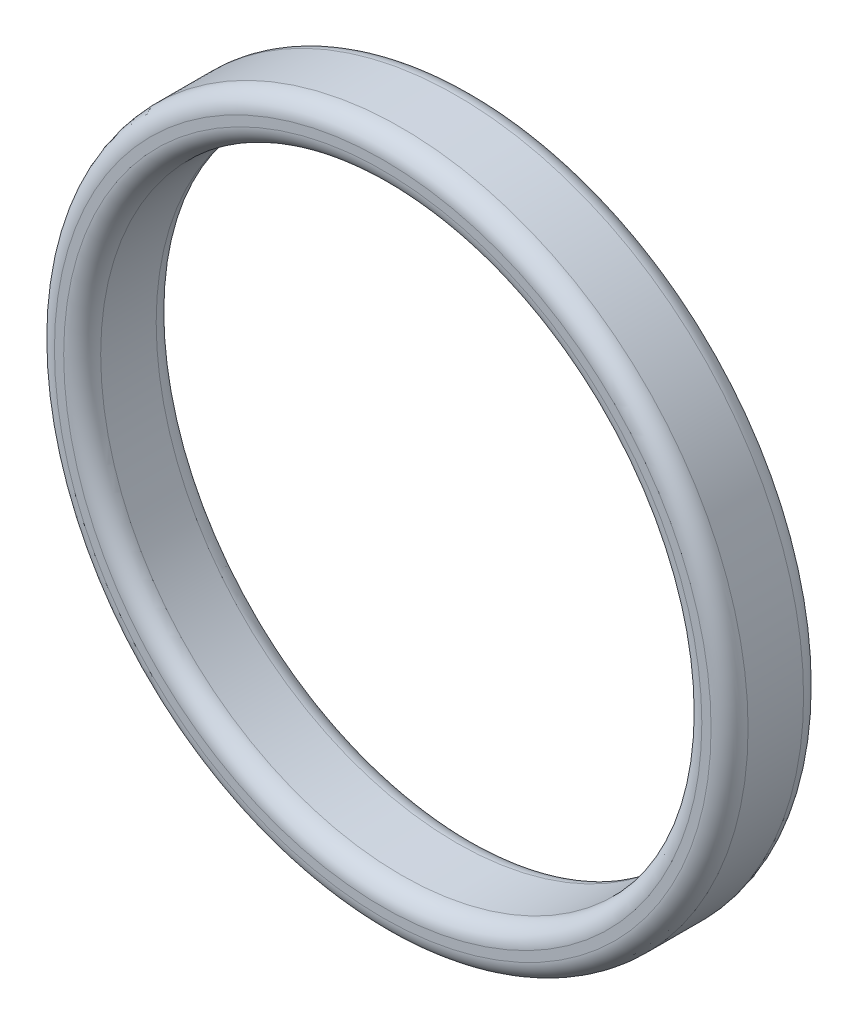
SolidWorks part; units mm, degrees
ref_plane "Alzado" through (0, 0, 0) normal (0, 0, 1) x (1, 0, 0)
ref_plane "Planta" through (0, 0, 0) normal (0, 1, 0) x (1, 0, 0)
ref_plane "Vista lateral" through (0, 0, 0) normal (1, 0, 0) x (0, 0, -1)
sketch "Croquis1" plane through (0, 0, 0) normal (0, 0, 1) x (1, 0, 0)
  circle A0 centre (0, 0) radius 0.15
  dimension "D1" = 0.3
extrude "Extruir-Lámina1" add sketch "Croquis1" along normal mid plane 0.04 thin thin type one direction reverse wall 0.02
fillet "Redondeo1" radius 0.008 4 edges at (0.15, 0, -0.02) (0.15, 0, 0.02) (0.13, 0, -0.02) (0.13, 0, 0.02)
